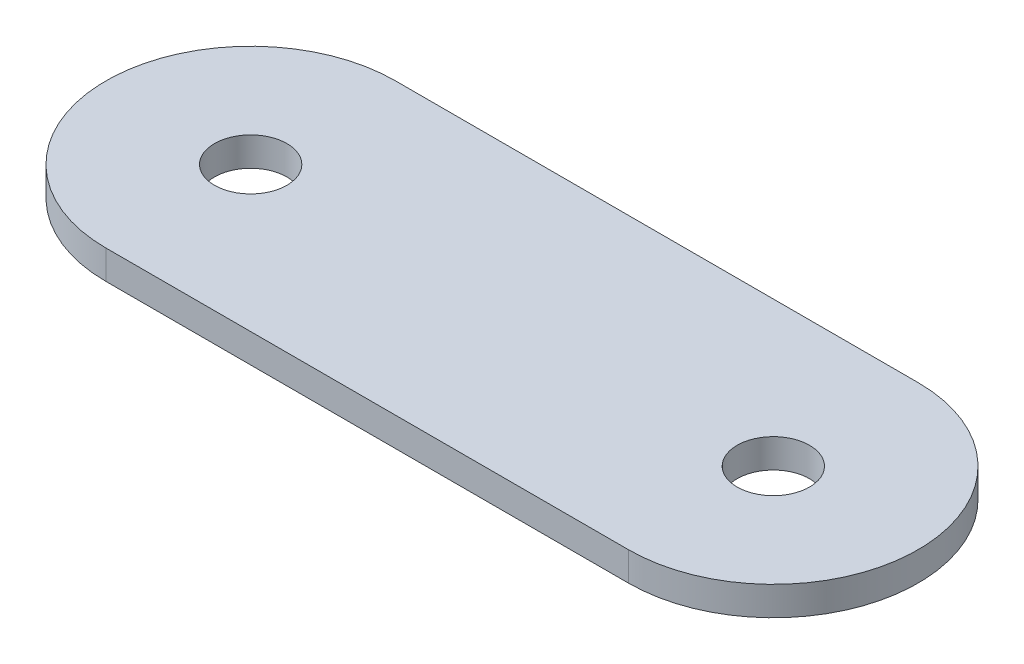
SolidWorks part; units mm, degrees
material "1060 Alaşım"
ref_plane "Ön Düzlem" through (0, 0, 0) normal (0, 0, 1) x (1, 0, 0)
ref_plane "Üst Düzlem" through (0, 0, 0) normal (0, 1, 0) x (1, 0, 0)
ref_plane "Sağ Düzlem" through (0, 0, 0) normal (1, 0, 0) x (0, 0, -1)
sketch "Çizim1" plane through (0, 0, 0) normal (0, 1, 0) x (1, 0, 0)
  line L0 (-18.05, 0) -> (18.05, 0) construction
  line L1 (-18.05, 10) -> (18.05, 10)
  line L2 (-18.05, -10) -> (18.05, -10)
  arc A0 (-18.05, 10) -> (-18.05, -10) centre (-18.05, 0) ccw
  arc A1 (18.05, -10) -> (18.05, 10) centre (18.05, 0) ccw
  circle A2 centre (-18.05, 0) radius 2.5
  circle A3 centre (18.05, 0) radius 2.5
  point P2 (0, 0)
  dimension "D2" = 10
  dimension "D3" = 5
  dimension "D4" = 5
  dimension "D1" = 36.1
extrude "Yükseklik-Ekstrüzyon1" add sketch "Çizim1" along normal blind 2
